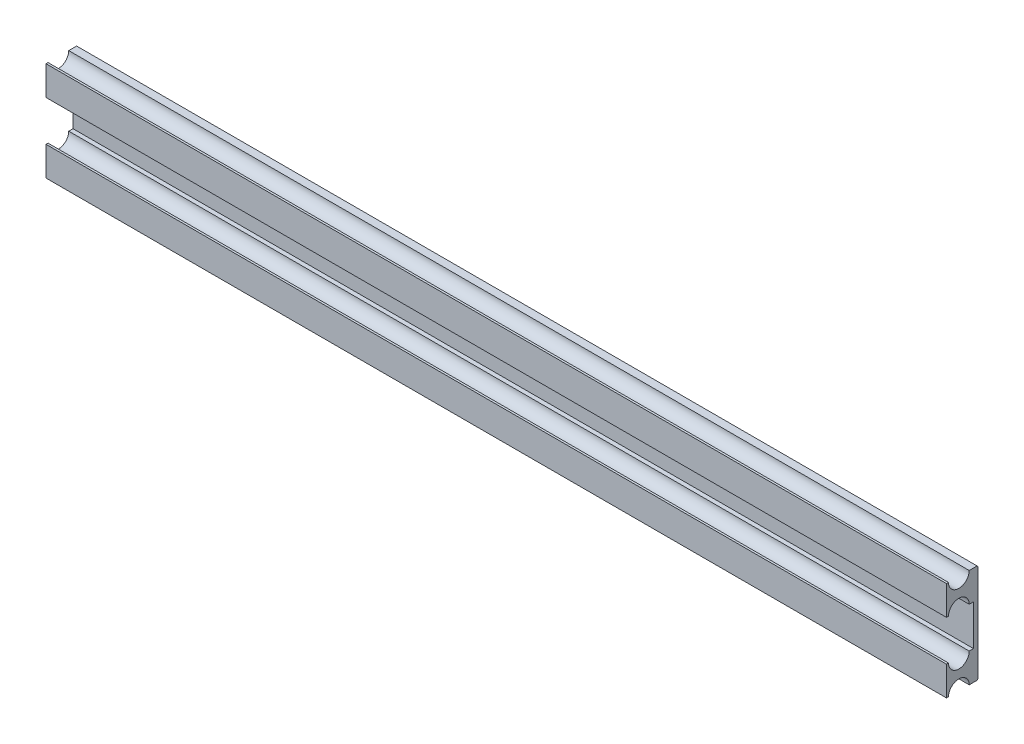
SolidWorks part; units mm, degrees
ref_plane "Front" through (0, 0, 0) normal (0, 0, 1) x (1, 0, 0)
ref_plane "Top" through (0, 0, 0) normal (0, 1, 0) x (1, 0, 0)
ref_plane "Right" through (0, 0, 0) normal (1, 0, 0) x (0, 0, -1)
sketch "Sketch1" plane through (0, 0, 0) normal (0, 0, 1) x (1, 0, 0)
  line L0 (-100, -4) -> (-100, 4) construction
  line L1 (100, 11) -> (-100, 11)
  line L2 (100, 11) -> (100, -11)
  line L3 (100, -11) -> (-100, -11)
  line L4 (-100, 11) -> (-100, -11)
  line L5 (100, 11) -> (-100, -11) construction
  line L6 (100, -11) -> (-100, 11) construction
  line L8 (100, 4) -> (-100, 4) construction
  point P0 (0, 0)
  dimension "D1" = 7
extrude "Boss-Extrude1" add sketch "Sketch1" against normal blind 1
sketch "Sketch2" plane through (0, 0, 0) normal (0, 0, 1) x (1, 0, 0)
  line L0 (-100, 11) -> (-100, -11) construction
  line L1 (100, 11) -> (-100, 11)
  line L2 (100, 11) -> (100, 4.5)
  line L3 (100, 4.5) -> (-100, 4.5)
  line L4 (-100, 11) -> (-100, 4.5)
  line L5 (100, -11) -> (100, 11) construction
  line L6 (100, -11) -> (-100, -11)
  line L7 (100, -11) -> (100, -4.5)
  line L8 (100, -4.5) -> (-100, -4.5)
  line L9 (-100, -11) -> (-100, -4.5)
  line L11 (100, 4) -> (-100, 4) construction
  dimension "D1" = 0.5
extrude "Boss-Extrude2" add sketch "Sketch2" along normal offset from surface (6 mm away) 1
ref_plane "Center of Slots" through (0, 7.75, 0) normal (0, -1, 0) x (-1, 0, 0)
sketch "Sketch5" plane through (0, 0, 0) normal (1, 0, 0) x (0, 0, -1)
  circle A1 centre (-3.25, 4.5) radius 2.3
  circle A2 centre (-3.25, 4.5) radius 2.3
  dimension "D1" = 0
extrude "Slot 1" cut sketch "Sketch5" against normal through all both and the other way through all
mirror "Slot 1x2" about plane through (0, 7.75, 0) normal (0, -1, 0) of "Slot 1"
mirror "Slot 2" about plane through (0, 0, 0) normal (0, 1, 0) of "Slot 1x2", "Slot 1"
chamfer "Deburs" distance 0.2 angle 45 2 edges at (0, -11, -1) (0, 11, -1)
